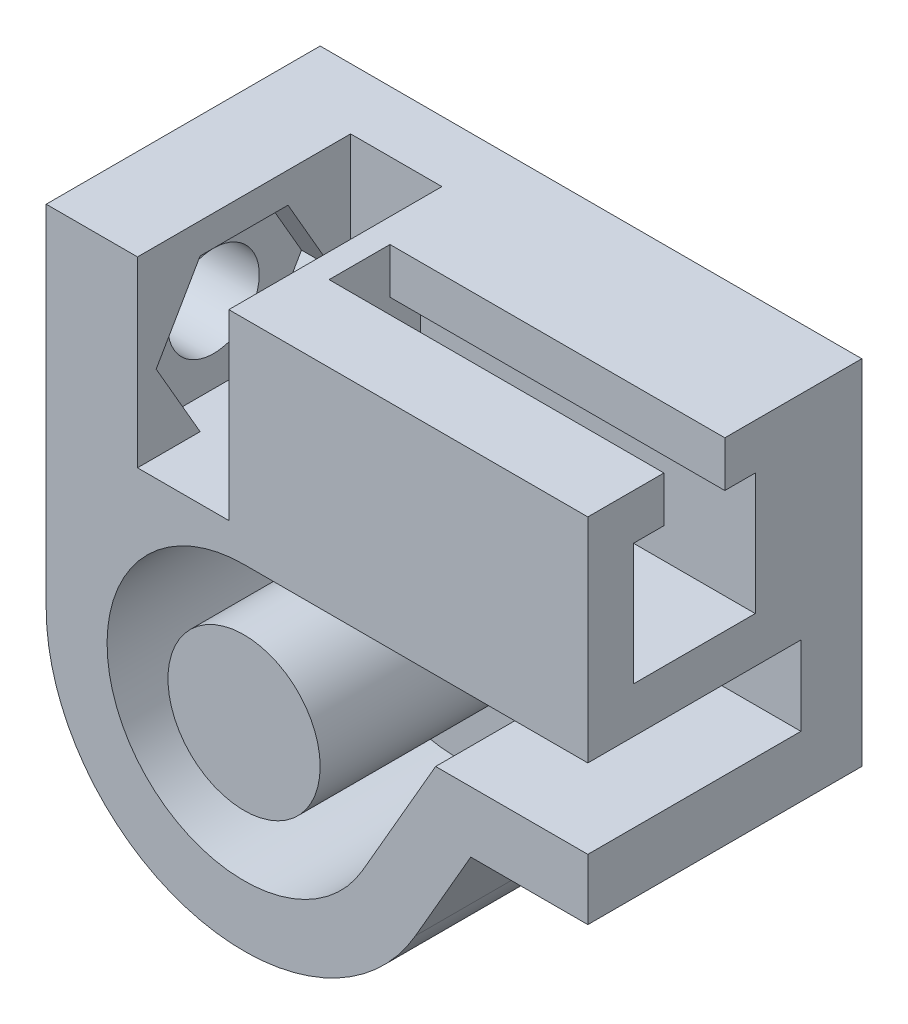
SolidWorks part; units mm, degrees
ref_plane "Plano frontal" through (0, 0, 0) normal (0, 0, 1) x (1, 0, 0)
ref_plane "Plano superior" through (0, 0, 0) normal (0, 1, 0) x (1, 0, 0)
ref_plane "Plano direito" through (0, 0, 0) normal (1, 0, 0) x (0, 0, -1)
sketch "Esboço1" plane through (0, 0, 0) normal (0, 0, 1) x (1, 0, 0)
  line L0 (0, 4.5) -> (11.2931, 4.5)
  line L1 (11.2931, 4.5) -> (11.2931, 6.5)
  line L2 (-3.5, 11.5) -> (-3.5, 5.5)
  line L3 (3.8971, -2.25) -> (6.2931, 1.9)
  line L4 (7.4478, -0.1) -> (11.2931, -0.1)
  line L5 (7.4478, -0.1) -> (5.6292, -3.25)
  line L6 (6.2931, 1.9) -> (11.2931, 1.9)
  line L7 (11.2931, -0.1) -> (11.2931, 1.9)
  line L8 (11.2931, 6.5) -> (11.2931, 11.5)
  line L9 (11.2931, 11.5) -> (-0.5, 11.5)
  line L10 (-6.5, 11.5) -> (-6.5, 0)
  line L11 (-3.5, 5.5) -> (-0.5, 5.5)
  line L12 (-0.5, 5.5) -> (-0.5, 11.5)
  line L13 (-3.5, 11.5) -> (-6.5, 11.5)
  circle A0 centre (0, 0) radius 2.5
  arc A1 (0, 4.5) -> (3.8971, -2.25) centre (0, 0) ccw
  arc A2 (-6.5, 0) -> (5.6292, -3.25) centre (0, 0) ccw
  point P16 (11.2931, 6.7651)
  dimension "D1" = 5
  dimension "D2" = 2
  dimension "D3" = 2
  dimension "D4" = 2.6
  dimension "D5" = 60
  dimension "D6" = 5
  dimension "D7" = 7
  dimension "D8" = 6
  dimension "D9" = 3
  dimension "D10" = 3
  dimension "D11" = 2
extrude "Ressalto-extrusão1" add sketch "Esboço1" along normal blind 7 contours A0 | A1 L3 L6 L7 L4 L5 A2 L10 L13 L2 L11 L12 L9 L8 L1 L0
sketch "Esboço2" plane through (-3.5, 0, 0) normal (1, 0, 0) x (0, 0, -1)
  line L0 (-3.5, 5.5) -> (-3.5, 8) construction
  line L1 (-7, 5.5) -> (0, 5.5) construction
  line L3 (-0.6132, 8) -> (-2.0566, 10.5)
  line L4 (-2.0566, 10.5) -> (-4.9434, 10.5)
  line L5 (-4.9434, 10.5) -> (-6.3868, 8)
  line L6 (-6.3868, 8) -> (-4.9434, 5.5)
  line L7 (-4.9434, 5.5) -> (-2.0566, 5.5)
  line L8 (-2.0566, 5.5) -> (-0.6132, 8)
  circle A0 centre (-3.5, 8) radius 2.5 construction
  point P4 (0, 0)
  point P12 (-6, 10.0855)
  point P13 (-4.2668, 5.7268)
  dimension "D1" = 5
extrude "Corte-extrusão1" cut sketch "Esboço2" against normal blind 1
sketch "Esboço4" plane through (-4.5, 0, 0) normal (1, 0, 0) x (0, 0, -1)
  line L0 (-4.9434, 10.5) -> (-2.0566, 5.5) construction
  line L1 (-4.9434, 10.5) -> (-6.3868, 8) construction
  line L2 (-2.0566, 10.5) -> (-4.9434, 10.5) construction
  circle A0 centre (-3.5, 8) radius 1.5
  point P7 (-4.9434, 10.5)
  point P10 (-4.9434, 10.5)
  dimension "D1" = 3
extrude "Corte-extrusão2" cut sketch "Esboço4" against normal through all both and the other way through all
sketch "Esboço5" plane through (11.2931, 0, 0) normal (1, 0, 0) x (0, 0, -1)
  line L0 (-3.5, 10) -> (-3.5, 11.5) construction
  line L1 (-5.5, 10) -> (-4.5, 10)
  line L2 (-5.5, 10) -> (-5.5, 6)
  line L4 (-5.5, 6) -> (-1.5, 6)
  line L5 (-1.5, 10) -> (-1.5, 6)
  line L6 (-5.5, 10) -> (-1.5, 6) construction
  line L7 (-5.5, 6) -> (-1.5, 10) construction
  line L8 (-7, 11.5) -> (0, 11.5) construction
  line L9 (-2.5, 10) -> (-2.5, 11.5)
  line L10 (-4.5, 10) -> (-4.5, 11.5)
  line L11 (-4.5, 11.5) -> (-2.5, 11.5)
  line L12 (-2.5, 10) -> (-1.5, 10)
  point P0 (-3.5, 8)
  dimension "D1" = 4
  dimension "D3" = 2
  dimension "D4" = 4
extrude "Corte-extrusão3" cut sketch "Esboço5" against normal blind 11
sketch "Esboço6" plane through (0, 0, 7) normal (0, 0, 1) x (1, 0, 0)
  line L0 (11.2931, 11.5) -> (-6.5, 11.5)
  line L1 (-6.5, 11.5) -> (-6.5, 0)
  line L2 (11.2931, 11.5) -> (11.2931, -0.1)
  line L3 (11.2931, -0.1) -> (7.4478, -0.1)
  line L4 (7.4478, -0.1) -> (5.6292, -3.25)
  arc A0 (5.6292, -3.25) -> (-6.5, 0) centre (0, 0) cw
  line M1 (0, 4.5) -> (11.2931, 4.5)
  line M2 (11.2931, 4.5) -> (11.2931, 11.5)
  line M3 (11.2931, 11.5) -> (-0.5, 11.5)
  line M4 (-0.5, 11.5) -> (-0.5, 5.5)
  line M5 (-0.5, 5.5) -> (-3.5, 5.5)
  line M6 (-3.5, 5.5) -> (-3.5, 11.5)
  line M7 (-3.5, 11.5) -> (-6.5, 11.5)
  line M8 (-6.5, 11.5) -> (-6.5, 0)
  arc M9 (-6.5, 0) -> (5.6292, -3.25) centre (0, 0) ccw
  line M10 (5.6292, -3.25) -> (7.4478, -0.1)
  line M11 (7.4478, -0.1) -> (11.2931, -0.1)
  line M12 (11.2931, -0.1) -> (11.2931, 1.9)
  line M13 (11.2931, 1.9) -> (6.2931, 1.9)
  line M14 (6.2931, 1.9) -> (3.8971, -2.25)
  arc M15 (3.8971, -2.25) -> (0, 4.5) centre (0, 0) cw
extrude "Ressalto-extrusão5" add sketch "Esboço6" against normal blind 2 from offset 7 contours L2 M1 M15 M14 M13 | M15 M1 M2 M3 M4 M5 M6 M7 M8 M9 M10 M11 M12 M13 M14 | L0 M4 M6 M5
